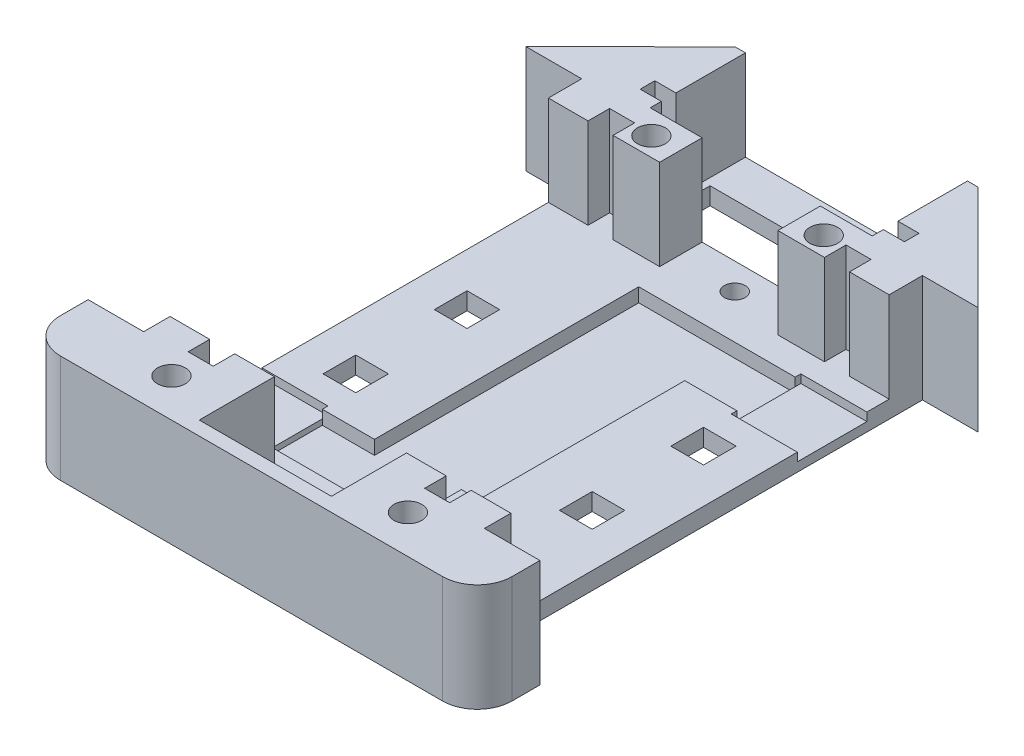
SolidWorks part; units mm, degrees
ref_plane "Front Plane" through (0, 0, 0) normal (0, 0, 1) x (1, 0, 0)
ref_plane "Top Plane" through (0, 0, 0) normal (0, 1, 0) x (1, 0, 0)
ref_plane "Right Plane" through (0, 0, 0) normal (1, 0, 0) x (0, 0, -1)
sketch "Sketch1" plane through (0, 0, 0) normal (0, 1, 0) x (1, 0, 0)
  line L1 (-35, -42.5) -> (35, -42.5)
  line L2 (-35, -42.5) -> (-35, 42.5)
  line L3 (-35, 42.5) -> (35, 42.5)
  line L4 (35, -42.5) -> (35, 42.5)
  line L5 (-35, -42.5) -> (35, 42.5) construction
  line L6 (-35, 42.5) -> (35, -42.5) construction
  point P0 (0, 0)
  dimension "D1" = 70
  dimension "D2" = 85
extrude "Boss-Extrude1" add sketch "Sketch1" along normal blind 2.5
sketch "Sketch2" plane through (0, 0, 0) normal (0, -1, 0) x (-1, 0, 0)
  line L0 (0, 42.5) -> (0, -42.5) construction
  line L1 (-35, 42.5) -> (35, 42.5) construction
  line L2 (35, -42.5) -> (-35, -42.5) construction
  line L3 (-35, 25.5) -> (-24.5, 25.5)
  line L4 (-35, -42.5) -> (-35, 42.5) construction
  line L5 (-24.5, 25.5) -> (-24.5, -34.5)
  line L6 (-24.5, -34.5) -> (-35, -34.5)
  line L7 (-35, -34.5) -> (-35, 25.5)
  line L10 (35, -34.5) -> (35, 25.5)
  line L11 (24.5, -34.5) -> (35, -34.5)
  line L12 (24.5, 25.5) -> (24.5, -34.5)
  line L13 (35, 25.5) -> (24.5, 25.5)
  dimension "D1" = 10.5
  dimension "D2" = 60
  dimension "D3" = 8
extrude "Cut-Extrude1" cut sketch "Sketch2" against normal blind 10
sketch "Sketch3" plane through (0, 2.5, 0) normal (0, 1, 0) x (1, 0, 0)
  line L0 (17.4625, 42.5) -> (35, 42.5)
  line L1 (35, 42.5) -> (-35, 42.5) construction
  line L2 (35, 42.5) -> (35, 25.5)
  line L3 (35, 25.5) -> (32.4849, 25.5)
  line L4 (32.485, 27.49) -> (32.48, -42.5) construction
  line L5 (24.5, 25.5) -> (35, 25.5) construction
  line L6 (32.4849, 25.5) -> (32.485, 27.49)
  line L7 (32.485, 27.49) -> (17.4625, 42.5)
  line L8 (0, -42.5) -> (0, 42.5) construction
  line L9 (-35, -42.5) -> (35, -42.5) construction
  line L10 (35, -34.5) -> (32.4806, -34.5)
  line L11 (35, -34.5) -> (24.5, -34.5) construction
  line L12 (32.4806, -34.5) -> (32.4806, -42.5)
  line L13 (32.4806, -42.5) -> (35, -42.5)
  line L14 (35, -42.5) -> (35, -34.5)
  line L15 (-35, -42.5) -> (-35, -34.5)
  line L16 (-32.4806, -42.5) -> (-35, -42.5)
  line L17 (-32.4806, -34.5) -> (-32.4806, -42.5)
  line L18 (-35, -34.5) -> (-32.4806, -34.5)
  line L19 (-32.485, 27.49) -> (-17.4625, 42.5)
  line L20 (-32.4849, 25.5) -> (-32.485, 27.49)
  line L21 (-35, 25.5) -> (-32.4849, 25.5)
  line L22 (-35, 42.5) -> (-35, 25.5)
  line L23 (-17.4625, 42.5) -> (-35, 42.5)
extrude "Cut-Extrude2" cut sketch "Sketch3" against normal blind 10
sketch "Sketch4" plane through (0, 0, 0) normal (0, -1, 0) x (-1, 0, 0)
  line L0 (0, 42.5) -> (0, 0) construction
  line L1 (-17.4625, 42.5) -> (17.4625, 42.5) construction
  line L2 (-19.35, 5.85) -> (-14.65, 5.85)
  line L3 (-19, 5.5) -> (-15, 5.5) construction
  line L4 (-19, 5.5) -> (-19, 1.5) construction
  line L5 (-19, 1.5) -> (-15, 1.5) construction
  line L6 (-15, 5.5) -> (-15, 1.5) construction
  line L7 (-19, -10.5) -> (-15, -10.5) construction
  line L8 (-19, -10.5) -> (-19, -14.5) construction
  line L9 (-19, -14.5) -> (-15, -14.5) construction
  line L10 (-15, -10.5) -> (-15, -14.5) construction
  line L11 (-14.65, 5.85) -> (-14.65, 1.15)
  line L12 (-19.35, 1.15) -> (-14.65, 1.15)
  line L13 (-19.35, 5.85) -> (-19.35, 1.15)
  line L14 (-19.35, -10.15) -> (-14.65, -10.15)
  line L15 (-14.65, -10.15) -> (-14.65, -14.85)
  line L16 (-19.35, -14.85) -> (-14.65, -14.85)
  line L17 (-19.35, -10.15) -> (-19.35, -14.85)
  line L18 (15, -10.5) -> (15, -14.5) construction
  line L19 (19, -14.5) -> (15, -14.5) construction
  line L20 (19, -10.5) -> (19, -14.5) construction
  line L21 (19, -10.5) -> (15, -10.5) construction
  line L22 (15, 5.5) -> (15, 1.5) construction
  line L23 (19, 1.5) -> (15, 1.5) construction
  line L24 (19, 5.5) -> (19, 1.5) construction
  line L25 (19, 5.5) -> (15, 5.5) construction
  line L26 (19.35, -10.15) -> (19.35, -14.85)
  line L27 (19.35, -14.85) -> (14.65, -14.85)
  line L28 (14.65, -10.15) -> (14.65, -14.85)
  line L29 (19.35, -10.15) -> (14.65, -10.15)
  line L30 (19.35, 5.85) -> (19.35, 1.15)
  line L31 (19.35, 1.15) -> (14.65, 1.15)
  line L32 (14.65, 5.85) -> (14.65, 1.15)
  line L33 (19.35, 5.85) -> (14.65, 5.85)
  line L34 (-14.75, 36.2) -> (14.75, 36.2) construction
  line L35 (14.75, 36.2) -> (14.75, 29) construction
  line L36 (14.75, 29) -> (-14.75, 29) construction
  line L37 (-14.75, 29) -> (-14.75, 36.2) construction
  line L38 (-14.95, 28.8) -> (-14.95, 36.4)
  line L39 (-14.95, 36.4) -> (14.95, 36.4)
  line L40 (14.95, 36.4) -> (14.95, 28.8)
  line L41 (14.95, 28.8) -> (-14.95, 28.8)
  dimension "D1" = 0.35
  dimension "D2" = 0.2
extrude "Cut-Extrude3" cut sketch "Sketch4" against normal blind 10
sketch "Sketch5" plane through (0, 2.5, 0) normal (0, 1, 0) x (1, 0, 0)
  line L1 (-32.485, 27.49) -> (-32.4849, 25.5)
  line L2 (-32.4849, 25.5) -> (-24.5, 25.5)
  line L3 (-32.4806, -42.5) -> (32.4806, -42.5) construction
  line L5 (-9.5, -42.5) -> (-9.5, -31.7)
  line L6 (-24.5, 25.5) -> (-24.5, -34.5) construction
  line L7 (-24.5, -31.7) -> (-18.8, -31.7)
  line L8 (-18.8, -31.7) -> (-18.8, -34.8)
  line L9 (-18.8, -34.8) -> (-15.2, -34.8)
  line L10 (-15.2, -34.8) -> (-15.2, -31.7)
  line L11 (-15.2, -31.7) -> (-9.5, -31.7)
  line L12 (-24.5, 25.5) -> (-24.5, 22.7)
  line L13 (-24.5, -31.7) -> (-24.5, -34.5)
  line L14 (0, -42.5) -> (0, 42.5) construction
  line L15 (17.4625, 42.5) -> (-17.4625, 42.5) construction
  line L17 (14.95, 28.8) -> (-14.95, 28.8) construction
  line L18 (-32.485, 27.49) -> (-17.4625, 42.5)
  line L20 (-15.9625, 28.8) -> (-8.5, 28.8)
  line L21 (-8.5, 28.8) -> (-8.5, 22.7)
  line L22 (-8.5, 22.7) -> (-15.2, 22.7)
  line L23 (-15.2, 22.7) -> (-15.2, 25.8)
  line L24 (-15.2, 25.8) -> (-18.8, 25.8)
  line L25 (-18.8, 25.8) -> (-18.8, 22.7)
  line L26 (-18.8, 22.7) -> (-24.5, 22.7)
  line L27 (-18.5, 22.5) -> (-24.5, 22.5) construction
  line L28 (-18.5, 22.5) -> (-18.5, 25.5) construction
  line L29 (-15.5, 22.5) -> (-15.5, 25.5) construction
  line L30 (-18.5, 25.5) -> (-15.5, 25.5) construction
  line L31 (-17.4625, 42.5) -> (-15.9625, 42.5)
  line L32 (-15.9625, 42.5) -> (-15.9625, 32.5)
  line L52 (-15.9625, 32.5) -> (-19, 32.5)
  line L53 (-19, 32.5) -> (-19, 30.4)
  line L54 (-19, 30.4) -> (-15.9625, 30.4)
  line L55 (-18.8, 32.25) -> (-15.8, 32.25) construction
  line L56 (-18.8, 30.65) -> (-18.8, 32.25) construction
  line L57 (-15.8, 30.65) -> (-18.8, 30.65) construction
  line L58 (-15.9625, 30.4) -> (-15.9625, 28.8)
  line L82 (-24.5, -34.5) -> (-32.4806, -34.5)
  line L83 (-32.4806, -34.5) -> (-32.4806, -42.5)
  line L84 (-32.4806, -42.5) -> (-9.5, -42.5)
  line L85 (32.4806, -42.5) -> (9.5, -42.5)
  line L86 (32.4806, -34.5) -> (32.4806, -42.5)
  line L87 (24.5, -34.5) -> (32.4806, -34.5)
  line L88 (15.9625, 30.4) -> (15.9625, 28.8)
  line L89 (19, 30.4) -> (15.9625, 30.4)
  line L90 (19, 32.5) -> (19, 30.4)
  line L91 (15.9625, 32.5) -> (19, 32.5)
  line L92 (15.9625, 42.5) -> (15.9625, 32.5)
  line L93 (17.4625, 42.5) -> (15.9625, 42.5)
  line L94 (18.8, 22.7) -> (24.5, 22.7)
  line L95 (18.8, 25.8) -> (18.8, 22.7)
  line L96 (15.2, 25.8) -> (18.8, 25.8)
  line L97 (15.2, 22.7) -> (15.2, 25.8)
  line L98 (8.5, 22.7) -> (15.2, 22.7)
  line L99 (8.5, 28.8) -> (8.5, 22.7)
  line L100 (15.9625, 28.8) -> (8.5, 28.8)
  line L101 (32.485, 27.49) -> (17.4625, 42.5)
  line L102 (24.5, -31.7) -> (24.5, -34.5)
  line L103 (24.5, 25.5) -> (24.5, 22.7)
  line L104 (15.2, -31.7) -> (9.5, -31.7)
  line L105 (15.2, -34.8) -> (15.2, -31.7)
  line L106 (18.8, -34.8) -> (15.2, -34.8)
  line L107 (18.8, -31.7) -> (18.8, -34.8)
  line L108 (24.5, -31.7) -> (18.8, -31.7)
  line L109 (9.5, -42.5) -> (9.5, -31.7)
  line L110 (32.4849, 25.5) -> (24.5, 25.5)
  line L111 (32.485, 27.49) -> (32.4849, 25.5)
  dimension "D2" = 10.8
  dimension "D4" = 3.6
  dimension "D5" = 15
  dimension "D6" = 0.2
  dimension "D7" = 0.3
  dimension "D8" = 0.3
  dimension "D9" = 0.3
  dimension "D10" = 16
  dimension "D12" = 1.5
  dimension "D13" = 0.25
  dimension "D14" = 0.2
  dimension "D15" = 0.25
  dimension "D16" = 3.1
extrude "Boss-Extrude2" add sketch "Sketch5" along normal blind 13
sketch "Sketch8" plane through (-24.5, 0, 0) normal (-1, 0, 0) x (0, 0, 1)
  line L0 (18.5, 2.5) -> (18.5, 1.3)
  line L1 (-22.7, 2.5) -> (31.7, 2.5) construction
  line L2 (18.5, 2) -> (18.5, 13) construction
  line L3 (18.5, 1.3) -> (28.5, 1.3)
  line L4 (28.5, 1.3) -> (28.5, 2.5)
  line L5 (28.5, 2) -> (28.5, 13) construction
  line L6 (28.5, 2.5) -> (18.5, 2.5)
  dimension "D1" = 1.2
extrude "Cut-Extrude6" cut sketch "Sketch8" against normal blind 9.5
sketch "Sketch9" plane through (-15, 0, 0) normal (-1, 0, 0) x (0, 0, 1)
  circle A0 centre (23.5, 7) radius 6.15
  dimension "D1" = 12.3
extrude "Cut-Extrude7" cut sketch "Sketch9" against normal blind 20
sketch "Sketch10" plane through (24.5, 0, 0) normal (1, 0, 0) x (0, 0, -1)
  line L0 (9.5, 2.5) -> (9.5, 1.3)
  line L1 (9.5, 2) -> (9.5, 13) construction
  line L2 (-31.7, 2.5) -> (22.7, 2.5) construction
  line L3 (9.5, 1.3) -> (19.5, 1.3)
  line L4 (19.5, 1.3) -> (19.5, 2.5)
  line L5 (19.5, 2) -> (19.5, 13) construction
  line L6 (9.5, 2.5) -> (19.5, 2.5)
  dimension "D1" = 1.2
extrude "Cut-Extrude8" cut sketch "Sketch10" against normal blind 9.5
sketch "Sketch11" plane through (15, 0, 0) normal (1, 0, 0) x (0, 0, -1)
  circle A0 centre (14.5, 7) radius 6.15
  dimension "D1" = 12.3
extrude "Cut-Extrude9" cut sketch "Sketch11" against normal blind 20
sketch "Sketch12" plane through (0, 2.5, 0) normal (0, 1, 0) x (1, 0, 0)
  line L8 (5, -19.308) -> (7.5, -19.308)
  line L9 (7.5, -19.308) -> (7.5, 10.308)
  line L10 (15, 10.308) -> (-5, 10.308) construction
  line L11 (7.5, 10.308) -> (-7.5, 10.308)
  line L12 (-7.5, 10.308) -> (-7.5, -19.308)
  line L13 (-15, -19.308) -> (5, -19.308) construction
  line L14 (-7.5, -19.308) -> (5, -19.308)
  line L15 (0, 10.308) -> (0, -19.308) construction
  dimension "D1" = 15
extrude "Cut-Extrude10" cut sketch "Sketch12" against normal blind 1.2
sketch "Sketch13" plane through (0, 2.5, 0) normal (0, 1, 0) x (1, 0, 0)
  line L0 (-5, 14.5) -> (5.9223, 14.5) construction
  line L1 (-5, 18.692) -> (-5, 10.308) construction
  line L2 (-2.3, 14.5) -> (-2.3, 10.308)
  line L3 (7.5, 10.308) -> (-5, 10.308) construction
  line L4 (-2.3, 10.308) -> (0.7, 10.308)
  line L5 (0.7, 10.308) -> (0.7, 14.5)
  line L6 (0.7, 14.5) -> (-2.3, 14.5)
  line L7 (5.1, -23.5) -> (-9.5, -23.5) construction
  line L8 (5.1, -28.25) -> (5.1, -18.75) construction
  line L9 (-9.5, -14.5) -> (-9.5, -31.5) construction
  line L10 (-0.7, -23.5) -> (-0.7, -19.308)
  line L11 (-7.5, -19.308) -> (5, -19.308) construction
  line L12 (-0.7, -19.308) -> (2.3, -19.308)
  line L13 (2.3, -19.308) -> (2.3, -23.5)
  line L14 (2.3, -23.5) -> (-0.7, -23.5)
  line L16 (1.8, -10) -> (1.8, -18.5) construction
  line L17 (-0.2, -18.5) -> (-0.2, -10) construction
  line L18 (0.2, 9.5) -> (0.2, 1) construction
  line L19 (-1.8, 1) -> (-1.8, 9.5) construction
  dimension "D1" = 0.5
  dimension "D2" = 0.5
  dimension "D3" = 0.5
  dimension "D4" = 0.5
extrude "Cut-Extrude11" cut sketch "Sketch13" against normal blind 1.2
sketch "Sketch15" plane through (0, 2.5, 0) normal (0, 1, 0) x (1, 0, 0)
  circle A0 centre (0, 25) radius 1.5
  circle A1 centre (0, -40) radius 1.5
extrude "Cut-Extrude12" cut sketch "Sketch15" against normal blind 10
sketch "Sketch16" plane through (0, 15.5, 0) normal (0, 1, 0) x (1, 0, 0)
  line L0 (0, 0) -> (0, 21.5166) construction
  line L1 (8.5, 28.8) -> (8.5, 22.7) construction
  line L2 (8.5, 22.7) -> (15.2, 22.7) construction
  line L5 (-17, -34.8) -> (-17, -42.5) construction
  line L6 (-15.2, -34.8) -> (-18.8, -34.8) construction
  line L7 (-32.4806, -42.5) -> (-9.5, -42.5) construction
  circle A0 centre (12.39, 25.4) radius 2
  circle A1 centre (17, -39) radius 2
  circle A2 centre (-17, -39) radius 2
  circle A3 centre (-12.39, 25.4) radius 2
  dimension "D1" = 4
  dimension "D2" = 3.5
  dimension "D3" = 3.89
  dimension "D4" = 2.7
extrude "Cut-Extrude13" cut sketch "Sketch16" against normal blind 10
sketch "Sketch17" plane through (0, 0, 0) normal (0, -1, 0) x (-1, 0, 0)
  line L0 (32.4806, -42.5) -> (-32.4806, -42.5)
  line L1 (-32.4806, -42.5) -> (-32.4806, -44.5)
  line L2 (-32.4806, -44.5) -> (32.4806, -44.5)
  line L3 (32.4806, -44.5) -> (32.4806, -42.5)
  dimension "D1" = 2
extrude "Boss-Extrude3" add sketch "Sketch17" against normal blind 15.5
fillet "Fillet1" radius 5 2 edges at (-32.4806, 7.75, 44.5) (32.4806, 7.75, 44.5)
sketch "Sketch18" plane through (0, 2.5, 0) normal (0, 1, 0) x (1, 0, 0)
  line L13 (-32.485, 27.49) -> (-24.5, 27.49)
  line L22 (0, 42.5) -> (0, 0) construction
  line L23 (24.5, 27.49) -> (24.5, -35.5)
  line L24 (24.5, -35.5) -> (32.485, -35.5)
  line L25 (15.9625, 42.5) -> (-15.9625, 42.5) construction
  line L26 (32.485, 27.49) -> (24.5, 27.49)
  line L27 (32.485, -35.5) -> (32.485, 27.49)
  line L28 (-32.485, 27.49) -> (-32.485, -35.5)
  line L29 (-32.485, -35.5) -> (-24.5, -35.5)
  line L30 (-24.5, -35.5) -> (-24.5, 27.49)
  line L31 (-24.5, -34.5) -> (-32.4806, -34.5) construction
  line L32 (27.4806, -44.5) -> (-27.4806, -44.5) construction
  line L33 (-24.5, -31.7) -> (-24.5, -34.5) construction
  line L34 (-32.4849, 25.5) -> (-24.5, 25.5) construction
  dimension "D1" = 1
  dimension "D2" = 9
  dimension "D3" = 1.99
extrude "Cut-Extrude14" cut sketch "Sketch18" against normal mid plane 100
sketch "Sketch19" plane through (0, 2.5, 0) normal (0, 1, 0) x (1, 0, 0)
  line L0 (15, 18.692) -> (-5, 18.692)
  line L1 (-5, 18.692) -> (-7.5, 18.692)
  line L2 (-7.5, 18.692) -> (-7.5, -19.308)
  line L3 (-15, -19.308) -> (-7.5, -19.308) construction
  line L4 (-7.5, 10.308) -> (-7.5, -19.308) construction
  line L5 (-7.5, -19.308) -> (-15, -19.308)
  line L6 (-15, -19.308) -> (-15, -27.692)
  line L7 (-15, -19.308) -> (-15, -21.1908) construction
  line L8 (-15, -18.5) -> (-15, -21.1908) construction
  line L9 (-15, -27.692) -> (5, -27.692)
  line L13 (7.5, -19.308) -> (7.5, 10.308)
  line L14 (7.5, 10.308) -> (15, 10.308)
  line L15 (15, 10.308) -> (15, 18.692)
  line L16 (5, -19.308) -> (5, -27.692)
  line L17 (2.3, -19.308) -> (7.5, -19.308) construction
  line L18 (7.5, -19.308) -> (5, -19.308)
extrude "Cut-Extrude15" cut sketch "Sketch19" against normal blind 2
